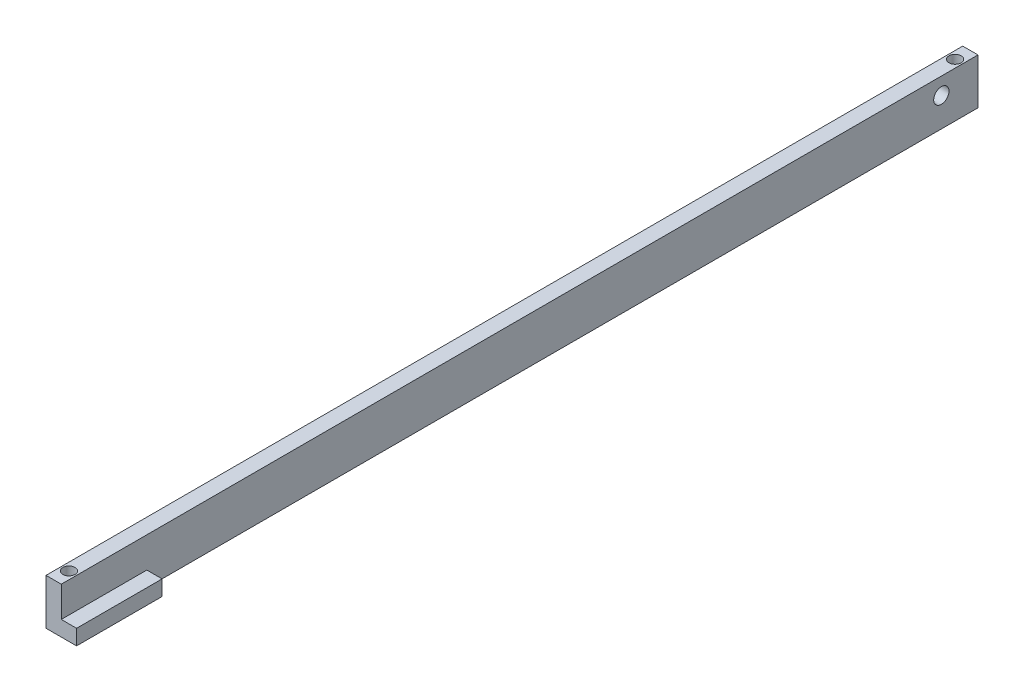
SolidWorks part; units mm, degrees
ref_plane "Front Plane" through (0, 0, 0) normal (0, 0, 1) x (1, 0, 0)
ref_plane "Top Plane" through (0, 0, 0) normal (0, 1, 0) x (1, 0, 0)
ref_plane "Right Plane" through (0, 0, 0) normal (1, 0, 0) x (0, 0, -1)
sketch "Sketch1" plane through (0, 0, 0) normal (0, 0, 1) x (1, 0, 0)
  line L0 (0, 0) -> (-12.7, 0)
  line L1 (-12.7, 0) -> (-12.7, 19.05)
  line L2 (-12.7, 19.05) -> (-6.35, 19.05)
  line L3 (-6.35, 19.05) -> (-6.35, 6.35)
  line L4 (-6.35, 6.35) -> (0, 6.35)
  line L5 (0, 6.35) -> (0, 0)
  dimension "D1" = 6.35
  dimension "D2" = 6.35
  dimension "D3" = 6.35
  dimension "D4" = 12.7
extrude "Boss-Extrude1" add sketch "Sketch1" against normal blind 381
sketch "Sketch2" plane through (-12.7, 0, 0) normal (-1, 0, 0) x (0, 0, 1)
  line L0 (-381, 0) -> (0, 0) construction
  line L2 (0, 19.05) -> (0, 0) construction
  circle A0 centre (-365.76, 12.065) radius 3.175
  dimension "D1" = 6.35
  dimension "D2" = 12.065
  dimension "D3" = 365.76
extrude "Cut-Extrude1" cut sketch "Sketch2" against normal up to next
sketch "Sketch3" plane through (0, 19.05, 0) normal (0, 1, 0) x (1, 0, 0)
  line L0 (-9.525, 381) -> (-9.525, 0) construction
  line L1 (-6.35, 381) -> (-12.7, 381) construction
  line L2 (-6.35, 0) -> (-12.7, 0) construction
  circle A0 centre (-9.525, 6.35) radius 2.54
  circle A1 centre (-9.525, 374.65) radius 2.54
  dimension "D1" = 5.08
  dimension "D3" = 6.35
  dimension "D2" = 6.35
extrude "Cut-Extrude2" cut sketch "Sketch3" against normal blind 7.62
sketch "Sketch4" plane through (0, 0, 0) normal (0, -1, 0) x (1, 0, 0)
  line L0 (-9.525, 0) -> (-9.525, -381) construction
  line L1 (-12.7, 0) -> (0, 0) construction
  line L2 (-12.7, -381) -> (0, -381) construction
  line L3 (0, -381) -> (0, 0) construction
  circle A0 centre (-9.525, -374.65) radius 2.54
  circle A1 centre (-9.525, -6.35) radius 2.54
  dimension "D2" = 5.08
  dimension "D1" = 9.525
  dimension "D3" = 6.35
  dimension "D4" = 6.35
extrude "Cut-Extrude3" cut sketch "Sketch4" against normal blind 7.62
sketch "Sketch5" plane through (0, 0, -381) normal (0, 0, -1) x (-1, 0, 0)
  line L1 (6.35, 6.35) -> (0, 6.35)
  line L2 (6.35, 6.35) -> (6.35, 0)
  line L3 (6.35, 0) -> (0, 0)
  line L4 (0, 6.35) -> (0, 0)
extrude "Cut-Extrude4" cut sketch "Sketch5" against normal blind 345.44
